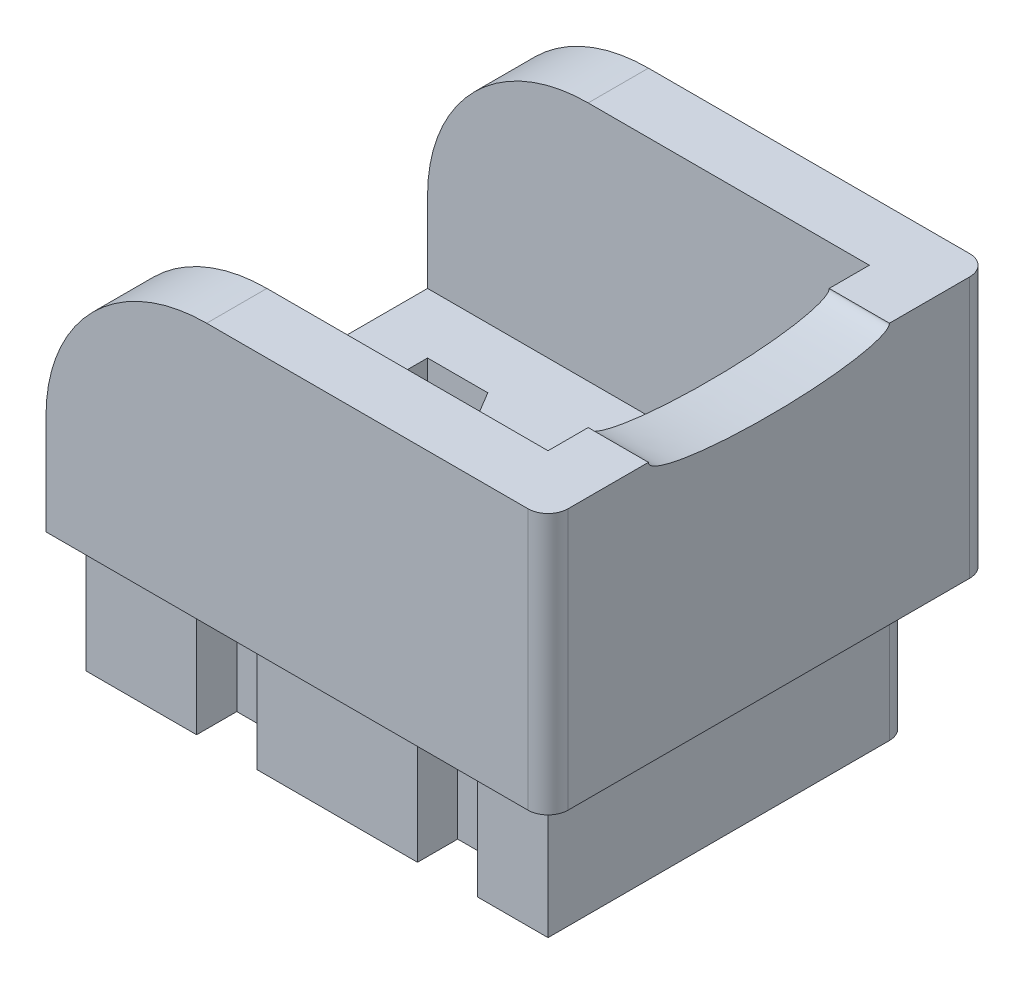
SolidWorks part; units mm, degrees
ref_plane "Front Plane" through (0, 0, 0) normal (0, 0, 1) x (1, 0, 0)
ref_plane "Top Plane" through (0, 0, 0) normal (0, 1, 0) x (1, 0, 0)
ref_plane "Right Plane" through (0, 0, 0) normal (1, 0, 0) x (0, 0, -1)
sketch "Sketch3" plane through (0, 0, 0) normal (0, 1, 0) x (1, 0, 0)
  line L0 (-5, 0.75) -> (0, 1.05) construction
  line L3 (0, -1.05) -> (-5, -0.75) construction
  line L4 (-2.5, 0.9) -> (-2, 0.93)
  line L6 (-4.25, 0) -> (-5.75, 0) construction
  line L7 (-2, 0.93) -> (-2, 0.56)
  line L8 (-2.5, 0.9) -> (-5, 0.9) construction
  line L9 (-2.5, 0.9) -> (-2.5, -0.9)
  line L10 (-2.5, -0.9) -> (-5, -0.9) construction
  line L11 (-5, 0.9) -> (-5, -0.9) construction
  line L12 (-2, 0.96) -> (-1.5, 0.96) construction
  line L13 (-2, 0.96) -> (-2, 0.56) construction
  line L14 (-2, 0.56) -> (-1.5, 0.56)
  line L15 (-1.5, 0.96) -> (-1.5, 0.56)
  line L16 (-1.5, -0.56) -> (-2, -0.56)
  line L17 (-1.5, -0.56) -> (-1.5, -0.96)
  line L18 (-1.5, -0.96) -> (-2, -0.96) construction
  line L19 (-2, -0.56) -> (-2, -0.96) construction
  line L21 (-2.5, -0.9) -> (-2, -0.93)
  line L22 (-2, -0.93) -> (-2, -0.56)
  line L23 (-1.5, 0.96) -> (0, 1.05)
  line L24 (0, -1.05) -> (-1.5, -0.96)
  circle A2 centre (0, 0) radius 0.6 construction
  circle A3 centre (0, 0) radius 0.4 construction
  circle A4 centre (-5, 0) radius 0.35 construction
  circle A5 centre (0, 0) radius 1.05 construction
  circle A6 centre (-5, 0) radius 0.75 construction
  arc A7 (-5, 0.9) -> (-5, -0.9) centre (-5, 0) ccw construction
  arc A8 (0, 1.05) -> (0, -1.05) centre (0, 0) cw
  point P4 (-2, -0.93)
  point P15 (-5, 0)
  point P16 (-2, 0.93)
  point P22 (-5, 0)
  dimension "D2" = 1.2
  dimension "D3" = 0.8
  dimension "D4" = 0.7
  dimension "D6" = 5
  dimension "D1" = 1.5
  dimension "D5" = 2.1
  dimension "D7" = 0.4
  dimension "D9" = 2.5
  dimension "D10" = 1.8
  dimension "D11" = 2.5
  dimension "D12" = 0.5
  dimension "D14" = 1.5
sketch "Sketch5" plane through (0, 0, 0) normal (0, 1, 0) x (1, 0, 0)
  line L0 (-2.25, 0) -> (1.75, 0) construction
  line L1 (-2.25, -2) -> (1.75, -2)
  line L2 (-2.25, -2) -> (-2.25, 2)
  line L3 (-2.25, 2) -> (1.75, 2)
  line L4 (1.75, -2) -> (1.75, 2) construction
  line L5 (-2.25, -2) -> (1.75, 2) construction
  line L6 (-2.25, 2) -> (1.75, -2) construction
  line L8 (1.75, 2) -> (3.25, 2)
  line L9 (3.25, 2) -> (3.25, -2)
  line L10 (3.25, -2) -> (1.75, -2)
  circle A1 centre (0, 0) radius 0.125 construction
  point P1 (-0.25, 0)
  dimension "D2" = 0.25
  dimension "D1" = 1.75
  dimension "D3" = 4
  dimension "D4" = 1.5
  dimension "D5" = 4
extrude "Boss-Extrude2" add sketch "Sketch5" against normal blind 2
sketch "Sketch6" plane through (0, 0, 0) normal (0, 0, 1) x (1, 0, 0)
  line L0 (3.25, 0.5) -> (3.25, 1.75)
  line L1 (3.25, 1.75) -> (1.75, 2.25)
  line L2 (1.75, 2.25) -> (1.75, 0.5)
  line L3 (1.75, 0.5) -> (3.25, 0.5)
  line L4 (2.5, 2) -> (2.1349, 0.9047)
  line L5 (1.75, 0.5) -> (1.75, 0) construction
  line L6 (3.25, 0.5) -> (3.25, 0) construction
  line L7 (1.75, 0) -> (3.25, 0) construction
  dimension "D1" = 1.25
  dimension "D2" = 1.75
  dimension "D3" = 0.5
ref_plane "Plane1" through (0.85, 2.55, 0) normal (0.3162, 0.9487, 0) x (0.9487, -0.3162, 0)
sketch "Sketch8" plane through (0.85, 2.55, 0) normal (0.3162, 0.9487, 0) x (0.9487, -0.3162, 0)
  line L0 (2.5298, 0) -> (0.9487, 0) construction
  line L2 (2.5298, 0) -> (1.8298, 0) construction
  circle A0 centre (1.8298, 0) radius 0.46
  dimension "D1" = 0.92
  dimension "D2" = 0.7
extrude "Cut-Extrude1" cut sketch "Sketch8" against normal through all
sketch "Sketch12" plane through (0, 0, 0) normal (0, 1, 0) x (1, 0, 0)
  line L0 (-2.25, 0) -> (1.75, 0) construction
  line L2 (-1.5, 1.25) -> (-1.5, -1.25)
  line L8 (-1.5, 0) -> (0, 0) construction
  line L9 (-1.5, -1.25) -> (-0.75, -1.25)
  line L10 (-0.75, -1.25) -> (0, 0)
  line L11 (0, 0) -> (-0.75, 1.25)
  line L12 (-0.75, 1.25) -> (-1.5, 1.25)
  dimension "D1" = 2.5
  dimension "D2" = 1.5
  dimension "D3" = 0.75
  dimension "D4" = 0.75
extrude "Cut-Extrude3" cut sketch "Sketch12" against normal through all
sketch "Sketch10" plane through (0, 0, 2) normal (0, 0, 1) x (1, 0, 0)
  line L0 (3.25, -2) -> (3.25, 3)
  line L1 (3.25, 3) -> (-2.25, 3)
  line L2 (-2.25, 3) -> (-2.25, 0)
  line L3 (-2.25, 0) -> (-2.25, -2)
  line L4 (-2.25, -2) -> (3.25, -2)
  dimension "D1" = 5
extrude "Boss-Extrude3" add sketch "Sketch10" along normal blind 0.75
mirror "Mirror1" about plane through (0, 0, 0) normal (0, 0, 1) of "Boss-Extrude3"
sketch "Sketch11" plane through (3.25, 0, 0) normal (1, 0, 0) x (0, 0, -1)
  line L0 (-2.75, 3) -> (2.75, 3)
  line L1 (2.75, 3) -> (2.75, -2)
  line L2 (2.75, -2) -> (-2.75, -2)
  line L3 (-2.75, -2) -> (-2.75, 3)
extrude "Boss-Extrude4" add sketch "Sketch11" along normal blind 0.75
fillet "Fillet1" radius 2 2 edges at (-2.25, 3, -2.375) (-2.25, 3, 2.375)
sketch "Sketch14" plane through (0, -2, 0) normal (0, -1, 0) x (1, 0, 0)
  line L0 (-2.25, 2.75) -> (-2.25, 2.25)
  line L1 (-2.25, -2.75) -> (-2.25, 2.75) construction
  line L2 (-2.25, 2.25) -> (3.5, 2.25)
  line L3 (3.5, 2.25) -> (3.5, -2.25)
  line L4 (3.5, -2.25) -> (-2.25, -2.25)
  line L5 (-2.25, -2.25) -> (-2.25, -2.75)
  line L6 (-2.25, -2.75) -> (4, -2.75)
  line L7 (4, -2.75) -> (4, 2.75)
  line L8 (4, 2.75) -> (-2.25, 2.75)
  line L9 (3.5, 0) -> (4, 0) construction
  line L10 (-2.25, 2) -> (1.75, 2) construction
  dimension "D1" = 0.25
extrude "Cut-Extrude5" cut sketch "Sketch14" against normal blind 1.75
sketch "Sketch13" plane through (0, 0, 2.25) normal (0, 0, 1) x (1, 0, 0)
  line L1 (-2.25, -2) -> (4, -2) construction
  line L7 (-0.5, -2) -> (2.25, -2) construction
  line L9 (-0.125, -0.25) -> (-0.875, -0.25)
  line L10 (-0.875, -0.25) -> (-0.875, -2)
  line L11 (-0.875, -2) -> (-0.125, -2)
  line L12 (-0.125, -2) -> (-0.125, -0.25)
  line L14 (2.625, -0.25) -> (1.875, -0.25)
  line L15 (1.875, -0.25) -> (1.875, -2)
  line L16 (1.875, -2) -> (2.625, -2)
  line L17 (2.625, -2) -> (2.625, -0.25)
  point P1 (0.875, -2)
  dimension "D1" = 0.75
  dimension "D2" = 1.75
  dimension "D3" = 2
extrude "Cut-Extrude4" cut sketch "Sketch13" against normal blind 0.5
mirror "Mirror2" about plane through (0, 0, 0) normal (0, 0, 1) of "Cut-Extrude4"
fillet "Fillet2" radius 0.25 8 edges at (3.5, -1.125, -2.25) (-1.5625, -0.25, -2.25) (0.875, -0.25, -2.25) (3.0625, -0.25, -2.25) (3.5, -0.25, 0) (3.0625, -0.25, 2.25) (0.875, -0.25, 2.25) (-1.5625, -0.25, 2.25)
fillet "Fillet3" radius 0.25 2 edges at (4, 1.375, 2.75) (4, 1.375, -2.75)
sketch "Sketch15" plane through (4, 0, 0) normal (1, 0, 0) x (0, 0, -1)
  line L1 (2.5, 3) -> (-2.5, 3) construction
  ellipse E0 centre (0, 3) end of major axis (1.5, 3) minor radius 0.25
  dimension "D1" = 1.5
  dimension "D2" = 0.25
extrude "Cut-Extrude6" cut sketch "Sketch15" against normal blind 10
